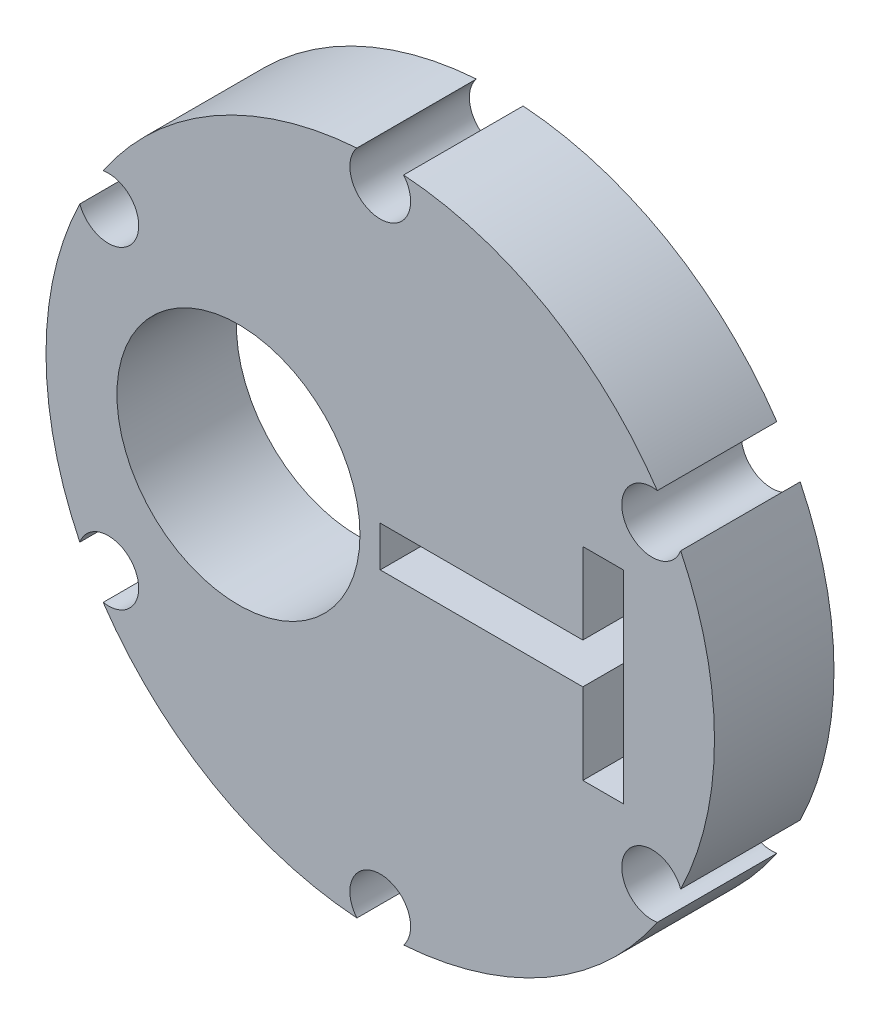
SolidWorks part; units mm, degrees
ref_plane "Front Plane" through (0, 0, 0) normal (0, 0, 1) x (1, 0, 0)
ref_plane "Top Plane" through (0, 0, 0) normal (0, 1, 0) x (1, 0, 0)
ref_plane "Right Plane" through (0, 0, 0) normal (1, 0, 0) x (0, 0, -1)
sketch "Sketch1" plane through (0, 0, 0) normal (0, 0, 1) x (1, 0, 0)
  circle A0 centre (0, 0) radius 16.5
  dimension "D1" = 33
extrude "Boss-Extrude1" add sketch "Sketch1" along normal blind 5.9
sketch "Sketch2" plane through (0, 0, 5.9) normal (0, 0, 1) x (1, 0, 0)
  circle A0 centre (0, 15.5) radius 1.5
  circle A1 centre (13.4234, 7.75) radius 1.5
  circle A2 centre (13.4234, -7.75) radius 1.5
  circle A3 centre (0, -15.5) radius 1.5
  circle A4 centre (-13.4234, -7.75) radius 1.5
  circle A5 centre (-13.4234, 7.75) radius 1.5
  point P15 (0, 0)
  dimension "D1" = 3
  dimension "D2" = 15.5
  dimension "D3" = 6
extrude "Cut-Extrude1" cut sketch "Sketch2" against normal through all
sketch "Sketch3" plane through (0, 0, 5.9) normal (0, 0, 1) x (1, 0, 0)
  line L0 (-7, 0) -> (0, 0) construction
  circle A0 centre (-7, 0) radius 6
  dimension "D1" = 12
  dimension "D3" = 7
extrude "Cut-Extrude2" cut sketch "Sketch3" against normal through all
sketch "Sketch5" plane through (0, 0, 5.9) normal (0, 0, 1) x (1, 0, 0)
  line L1 (12, 5) -> (10, 5)
  line L2 (12, 5) -> (12, -5)
  line L3 (12, -5) -> (10, -5)
  line L4 (10, 5) -> (10, 1)
  line L5 (10, -1) -> (10, -5)
  line L6 (0, 1) -> (10, 1)
  line L7 (0, 1) -> (0, -1)
  line L8 (0, -1) -> (10, -1)
  point P10 (0, 0)
  dimension "D1" = 10
  dimension "D2" = 2
extrude "Cut-Extrude3" cut sketch "Sketch5" against normal through all
equation "\"smallPulleyTeeth\"= 15"
equation "\"largePulleyTeeth\"= 30"
equation "\"eighthThick\"= 2.9mm"
equation "\"sixteenthThick\"= 1.7mm"
equation "\"wheelEighthThick\"=3.0mm"
equation "\"quarterThick\"=5.9mm"
equation "\"OD\"= 145mm"
equation "\"puckAngle\"= 60.5deg"
equation "\"puckDiam\"= 76.5mm"
equation "\"axlePress\"= 5.9mm"
equation "\"D1@Boss-Extrude1\"=\"quarterThick\""
